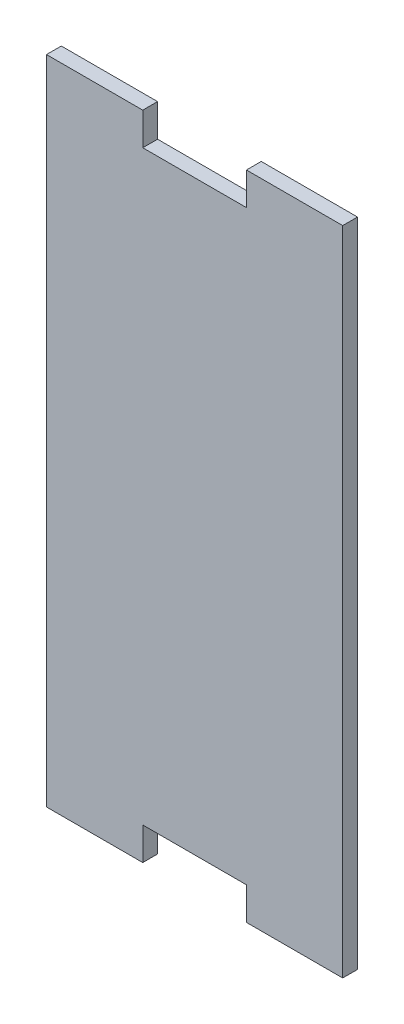
SolidWorks part; units mm, degrees
ref_plane "Front Plane" through (0, 0, 0) normal (0, 0, 1) x (1, 0, 0)
ref_plane "Top Plane" through (0, 0, 0) normal (0, 1, 0) x (1, 0, 0)
ref_plane "Right Plane" through (0, 0, 0) normal (1, 0, 0) x (0, 0, -1)
sketch "Sketch2" plane through (0, 0, 0) normal (0, 0, 1) x (1, 0, 0)
  line L1 (-5, -11) -> (5, -11)
  line L2 (-5, -11) -> (-5, 11)
  line L3 (-5, 11) -> (5, 11)
  line L4 (5, -11) -> (5, 11)
  line L5 (-5, -11) -> (5, 11) construction
  line L6 (-5, 11) -> (5, -11) construction
  point P0 (0, 0)
  dimension "D1" = 10
  dimension "D2" = 22
extrude "Boss-Extrude1" add sketch "Sketch2" along normal blind 0.5
sketch "Sketch4" plane through (0, 0, 0.5) normal (0, 0, 1) x (1, 0, 0)
  line L0 (5, 11) -> (-5, 11) construction
  line L1 (-1.75, 11) -> (1.75, 11)
  line L2 (-1.75, 11) -> (-1.75, 9.9)
  line L3 (-1.75, 9.9) -> (1.75, 9.9)
  line L4 (1.75, 11) -> (1.75, 9.9)
  dimension "D1" = 3.5
  dimension "D2" = 1.1
  dimension "D3" = 1.75
extrude "Cut-Extrude1" cut sketch "Sketch4" against normal through all
mirror "Mirror2" about plane through (0, 0, 0) normal (0, 1, 0) of "Cut-Extrude1"
